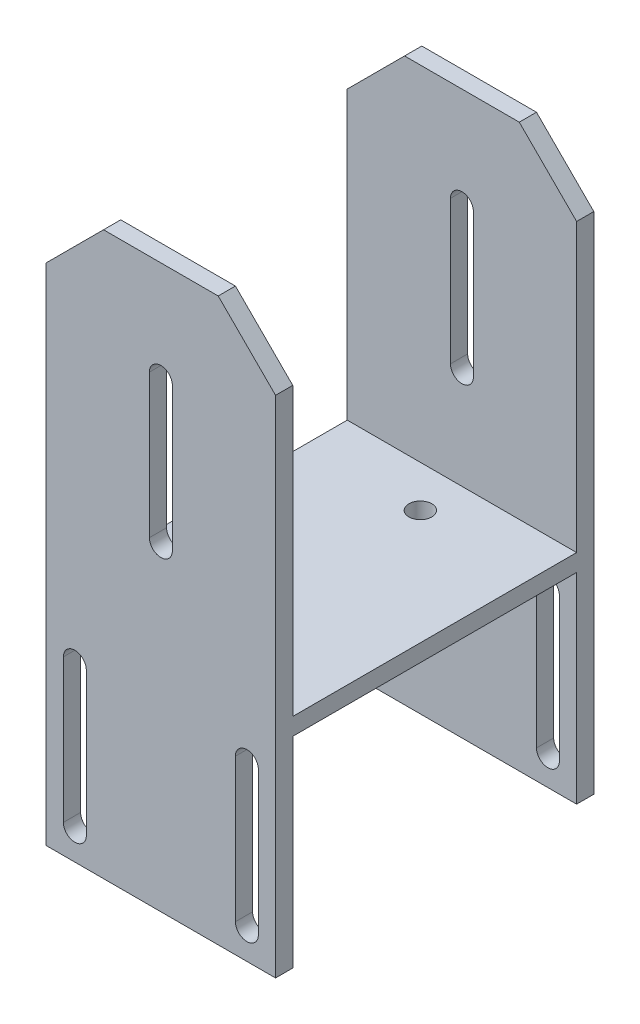
SolidWorks part; units mm, degrees
ref_plane "Alzado" through (0, 0, 0) normal (0, 0, 1) x (1, 0, 0)
ref_plane "Planta" through (0, 0, 0) normal (0, 1, 0) x (1, 0, 0)
ref_plane "Vista lateral" through (0, 0, 0) normal (1, 0, 0) x (0, 0, -1)
sketch "Croquis1" plane through (0, 0, 0) normal (1, 0, 0) x (0, 0, -1)
  line L0 (0, 0) -> (0, 98)
  line L1 (0, 98) -> (3, 98)
  line L2 (3, 98) -> (3, 38)
  line L3 (3, 38) -> (52.5, 38)
  line L4 (52.5, 38) -> (52.5, 98)
  line L5 (52.5, 98) -> (55.5, 98)
  line L6 (55.5, 98) -> (55.5, 0)
  line L7 (55.5, 0) -> (52.5, 0)
  line L8 (52.5, 0) -> (52.5, 35)
  line L9 (52.5, 35) -> (3, 35)
  line L10 (3, 35) -> (3, 0)
  line L11 (3, 0) -> (0, 0)
  dimension "D1" = 3
  dimension "D2" = 55.5
  dimension "D3" = 3
  dimension "D4" = 35
  dimension "D5" = 60
extrude "Saliente-Extruir1" add sketch "Croquis1" along normal blind 40
sketch "Croquis2" plane through (0, 38, 0) normal (0, 1, 0) x (1, 0, 0)
  line L0 (0, 27.75) -> (40, 27.75) construction
  line L1 (0, 52.5) -> (0, 3) construction
  line L2 (40, 52.5) -> (40, 3) construction
sketch "Croquis3" plane through (0, 0, 0) normal (0, 0, 1) x (1, 0, 0)
  line L0 (18, 80.5) -> (18, 55.5)
  line L2 (40, 98) -> (0, 98) construction
  line L3 (3, 30) -> (3, 5)
  line L4 (7, 30) -> (7, 5)
  line L5 (3, 17.5) -> (7, 17.5) construction
  line L6 (22, 80.5) -> (22, 55.5)
  line L7 (0, 98) -> (0, 0) construction
  line L8 (40, 0) -> (0, 0) construction
  line L9 (20, 0) -> (20, 98) construction
  line L10 (33, 30) -> (33, 5)
  line L11 (37, 30) -> (37, 5)
  line L12 (18, 68) -> (22, 68) construction
  arc A4 (3, 30) -> (7, 30) centre (5, 30) cw
  arc A5 (7, 5) -> (3, 5) centre (5, 5) cw
  arc A6 (37, 30) -> (33, 30) centre (35, 30) ccw
  arc A7 (33, 5) -> (37, 5) centre (35, 5) ccw
  arc A8 (18, 80.5) -> (22, 80.5) centre (20, 80.5) cw
  arc A9 (22, 55.5) -> (18, 55.5) centre (20, 55.5) cw
  point P2 (20, 68)
  point P16 (5, 17.5)
  dimension "D1" = 25
  dimension "D7" = 25
  dimension "D2" = 30
  dimension "D5" = 4
  dimension "D6" = 5
  dimension "D8" = 5
extrude "Cortar-Extruir1" cut sketch "Croquis3" against normal blind 79
chamfer "Chaflán1" distance 10 angle 45 4 edges at (40, 98, -1.5) (40, 98, -54) (0, 98, -54) (0, 98, -1.5)
sketch "Croquis6" plane through (0, 38, 0) normal (0, 1, 0) x (1, 0, 0)
  line L0 (20, 45.25) -> (20, 10.25) construction
  line L3 (20, 10.25) -> (20, 3) construction
  line L4 (30, 3) -> (10, 3) construction
  line L5 (20, 45.25) -> (20, 52.5) construction
  line L6 (30, 52.5) -> (10, 52.5) construction
  circle A0 centre (20, 45.25) radius 2
  circle A1 centre (20, 10.25) radius 2
  dimension "D1" = 4
  dimension "D2" = 35
extrude "Cortar-Extruir2" cut sketch "Croquis6" against normal blind 9
